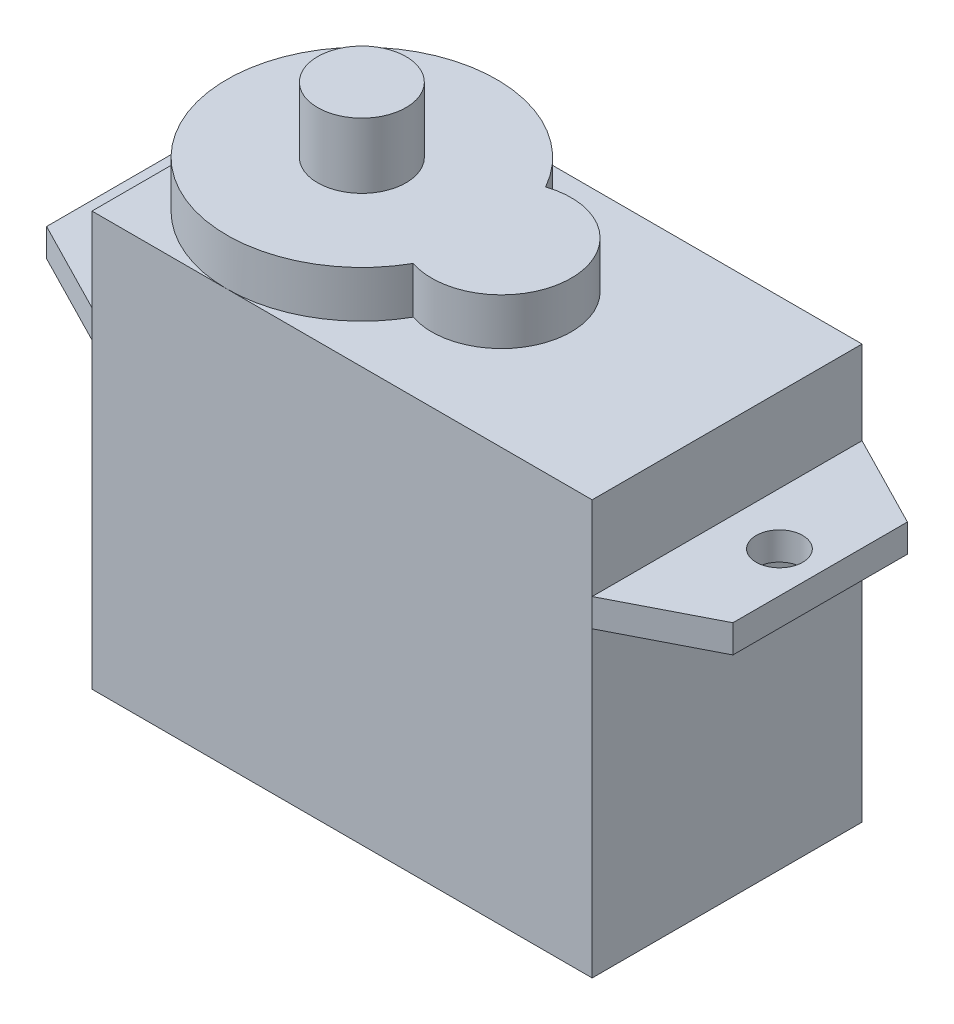
SolidWorks part; units mm, degrees
ref_plane "Front Plane" through (0, 0, 0) normal (0, 0, 1) x (1, 0, 0)
ref_plane "Top Plane" through (0, 0, 0) normal (0, 1, 0) x (1, 0, 0)
ref_plane "Right Plane" through (0, 0, 0) normal (1, 0, 0) x (0, 0, -1)
sketch "Sketch1" plane through (0, 0, 0) normal (0, 1, 0) x (1, 0, 0)
  line L1 (-10.75, 5.8) -> (10.75, 5.8)
  line L2 (-10.75, 5.8) -> (-10.75, -5.8)
  line L3 (-10.75, -5.8) -> (10.75, -5.8)
  line L4 (10.75, 5.8) -> (10.75, -5.8)
  line L5 (-10.75, 5.8) -> (10.75, -5.8) construction
  line L6 (-10.75, -5.8) -> (10.75, 5.8) construction
  point P0 (0, 0)
  dimension "D1" = 11.6
  dimension "D2" = 21.5
extrude "Boss-Extrude1" add sketch "Sketch1" along normal blind 13
sketch "Sketch2" plane through (0, 13, 0) normal (0, 1, 0) x (1, 0, 0)
  line L0 (-10.75, 5.8) -> (-14.75, 3.75)
  line L1 (-14.75, 3.75) -> (-14.75, -3.75)
  line L2 (-14.75, -3.75) -> (-10.75, -5.8)
  line L3 (0, 5.8) -> (0, -5.8) construction
  line L4 (10.75, -5.8) -> (10.75, 5.8)
  line L5 (10.75, 5.8) -> (-10.75, 5.8)
  line L6 (-10.75, 5.8) -> (-10.75, -5.8)
  line L7 (-10.75, -5.8) -> (10.75, -5.8)
  line L9 (10.75, 5.8) -> (-10.75, 5.8)
  line L11 (-10.75, -5.8) -> (10.75, -5.8)
  line L12 (10.75, 5.8) -> (14.75, 3.75)
  line L13 (14.75, -3.75) -> (10.75, -5.8)
  line L14 (14.75, 3.75) -> (14.75, -3.75)
  line L15 (-14.75, 0) -> (14.75, 0) construction
  line L16 (-10.75, 5.8) -> (-10.75, -5.8) construction
  circle A0 centre (-13, 0) radius 1
  circle A1 centre (13, 0) radius 1
  point P8 (-14.75, 0)
  dimension "D3" = 2
  dimension "D2" = 7.5
  dimension "D4" = 2.25
  dimension "D1" = 0
extrude "Boss-Extrude2" add sketch "Sketch2" along normal blind 1.2
sketch "Sketch3" plane through (0, 14.2, 0) normal (0, 1, 0) x (1, 0, 0)
  line L1 (-10.75, 5.8) -> (10.75, 5.8)
  line L2 (-10.75, 5.8) -> (-10.75, -5.8)
  line L3 (-10.75, -5.8) -> (10.75, -5.8)
  line L4 (10.75, 5.8) -> (10.75, -5.8)
extrude "Boss-Extrude3" add sketch "Sketch3" along normal blind 3.6
sketch "Sketch4" plane through (0, 17.8, 0) normal (0, 1, 0) x (1, 0, 0)
  line L0 (-10.75, 0) -> (10.75, 0) construction
  line L1 (-10.75, 5.8) -> (-10.75, -5.8) construction
  line L2 (10.75, -5.8) -> (10.75, 5.8) construction
  arc A1 (0.1033, 2.8467) -> (0.1033, -2.8467) centre (-4.95, 0) ccw
  arc A2 (0.1033, -2.8467) -> (0.1033, 2.8467) centre (1.05, 0) ccw
  dimension "D2" = 6
  dimension "D1" = 5.8
  dimension "D3" = 6
extrude "Boss-Extrude4" add sketch "Sketch4" along normal blind 2
sketch "Sketch5" plane through (0, 19.8, 0) normal (0, 1, 0) x (1, 0, 0)
  circle A0 centre (-4.95, 0) radius 1.9
  dimension "D1" = 3.8
extrude "Boss-Extrude5" add sketch "Sketch5" along normal blind 2.8
